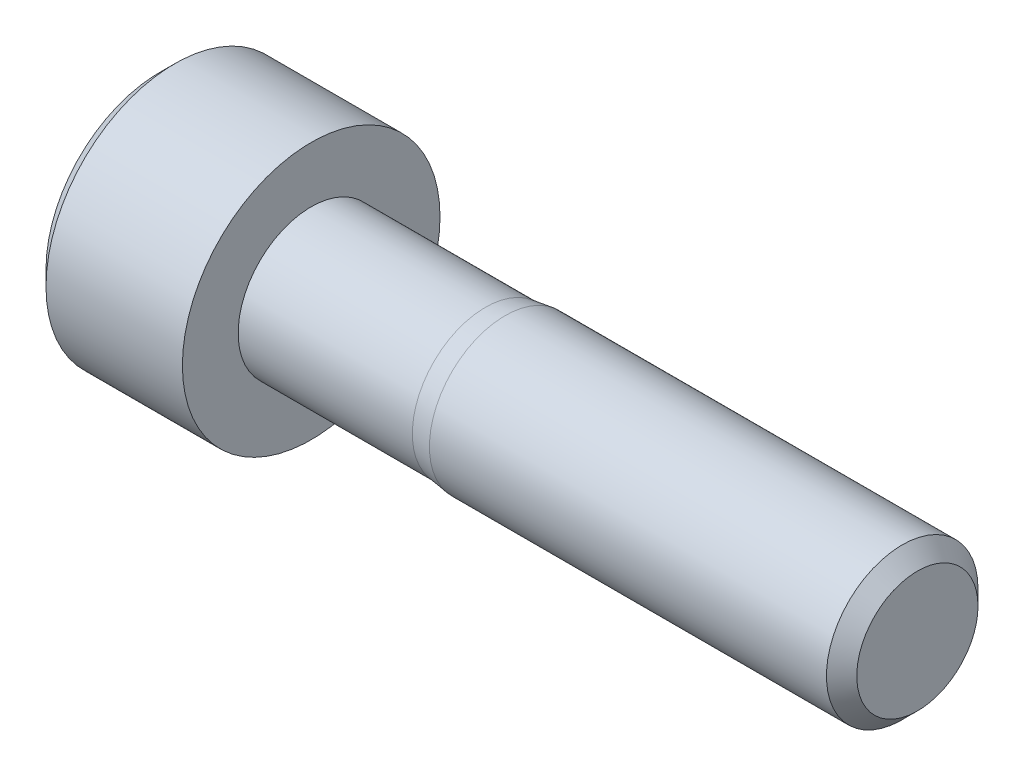
SolidWorks part; units mm, degrees
material "AISI 304"
ref_plane "Front Plane" through (0, 0, 0) normal (0, 0, 1) x (1, 0, 0)
ref_plane "Top Plane" through (0, 0, 0) normal (0, 1, 0) x (1, 0, 0)
ref_plane "Right Plane" through (0, 0, 0) normal (1, 0, 0) x (0, 0, -1)
ref_plane "Plane1" through (0, 0, 0) normal (0, 0, -1) x (-1, 0, 0)
sketch "Sketch1" plane through (0, 0, 0) normal (0, 0, -1) x (-1, 0, 0)
  line L0 (0, 4.25) -> (0, 0)
  line L1 (0, 0) -> (5, 0)
  line L2 (5, 0) -> (5, 4.25)
  line L3 (5, 4.25) -> (0, 4.25)
  line L4 (0, 0) -> (5, 0) construction
revolve "Revolve1" add sketch "Sketch1" angle 360 about L4
sketch "Sketch2" plane through (0, 0, 0) normal (1, 0, 0) x (0, 0, -1)
  circle A0 centre (0, 0) radius 2.41
extrude "Boss-Extrude1" add sketch "Sketch2" along normal blind 5.7468
sketch "Sketch3" plane through (5.7468, 0, 0) normal (1, 0, 0) x (0, 0, -1)
  circle A0 centre (0, 0) radius 2.41
extrude "Boss-Extrude2" add sketch "Sketch3" along normal blind 0.6532 draft 7.845 draft outward yes
sketch "Sketch4" plane through (6.4, 0, 0) normal (1, 0, 0) x (0, 0, -1)
  circle A0 centre (0, 0) radius 2.5
extrude "Boss-Extrude3" add sketch "Sketch4" along normal blind 13.6
sketch "Sketch5" plane through (-5, 0, 0) normal (-1, 0, 0) x (0, 0, 1)
  line L0 (-2, -1.1547) -> (0, -2.3094)
  line L1 (0, -2.3094) -> (2, -1.1547)
  line L2 (2, -1.1547) -> (2, 1.1547)
  line L3 (2, 1.1547) -> (0, 2.3094)
  line L4 (0, 2.3094) -> (-2, 1.1547)
  line L5 (-2, 1.1547) -> (-2, -1.1547)
extrude "Cut-Extrude1" cut sketch "Sketch5" against normal blind 2.5
sketch "Sketch6" plane through (0, 0, 0) normal (0, 0, 1) x (1, 0, 0)
  line L0 (-2.5, 2) -> (-2.5, 0)
  line L1 (-2.5, 0) -> (-1.3453, 0)
  line L2 (-1.3453, 0) -> (-2.5, 2)
  line L3 (-2.5, 0) -> (-1.3453, 0) construction
revolve "Cut-Revolve1" cut sketch "Sketch6" angle 360 about L3
chamfer "Chamfer1" distance 0.5 angle 45 2 edges at (20, 0, -2.5) (-5, 0, 4.25)
thread "Thread1" pitch 0.8 start angle 0, offset 0, length 0, pitch 0.8, diameter 5
ref_plane "Plane2" through (19.5, 0, 2.5) normal (0, -1, 0) x (0, 0, 1)
sketch "Thread Profile1" plane through (19.5, 0, 2.5) normal (0, -1, 0) x (0, 0, 1)
  line L0 (0, 0) -> (0, 0.8) construction
  line L11 (0, 0) -> (0, 0.7)
  line L12 (0, 0.7) -> (-0.433, 0.45)
  line L13 (-0.433, 0.45) -> (-0.433, 0.25)
  line L15 (-0.433, 0.25) -> (0, 0)
  line L17 (-0.433, 0.35) -> (0, 0.35) construction
  point P2 (0, 0)
  dimension "Pitch" = 0.8
  dimension "Profile_Angle" = 60
  dimension "Profile_Land" = 0.2
  dimension "Profile_Height" = 0.433
